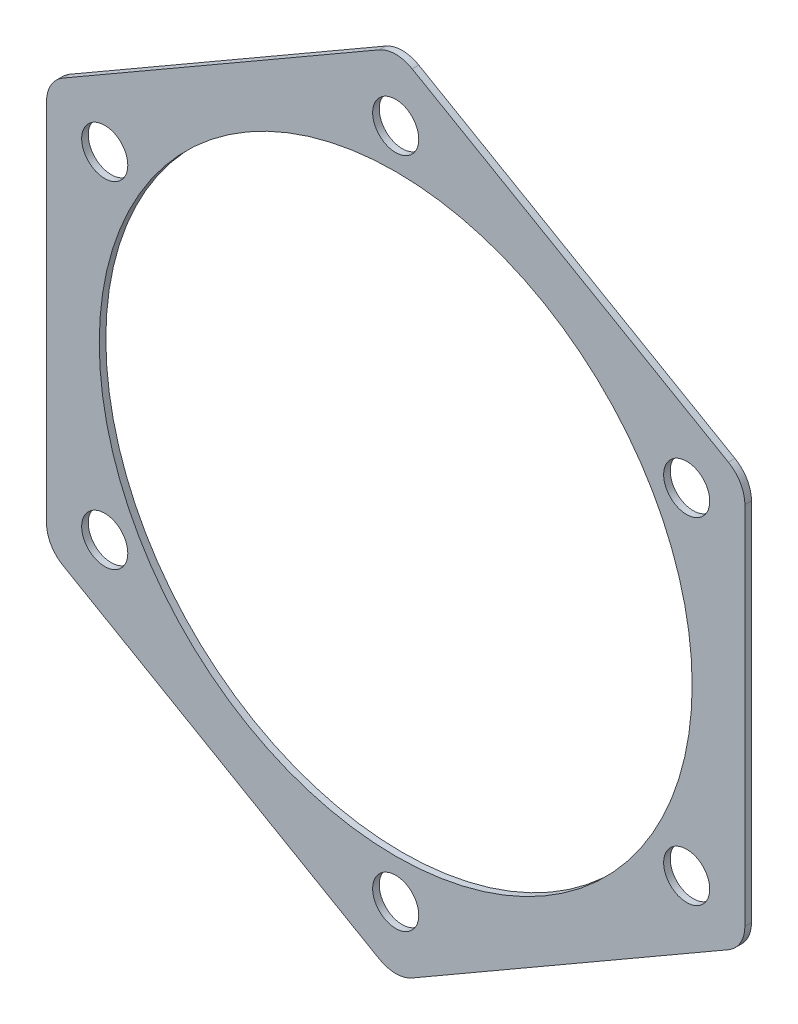
SolidWorks part; units mm, degrees
ref_plane "Front Plane" through (0, 0, 0) normal (0, 0, 1) x (1, 0, 0)
ref_plane "Top Plane" through (0, 0, 0) normal (0, 1, 0) x (1, 0, 0)
ref_plane "Right Plane" through (0, 0, 0) normal (1, 0, 0) x (0, 0, -1)
sketch "Sketch1" plane through (0, 0, 0) normal (0, 0, 1) x (1, 0, 0)
  line L0 (0, 61.1991) -> (0, -61.1991) construction
  line L1 (0, 61.1991) -> (-53, 30.5996)
  line L2 (-53, 30.5996) -> (-53, -30.5996)
  line L3 (-53, -30.5996) -> (0, -61.1991)
  line L4 (0, -61.1991) -> (53, -30.5996)
  line L5 (53, -30.5996) -> (53, 30.5996)
  line L6 (53, 30.5996) -> (0, 61.1991)
  line L7 (-53, 0) -> (53, 0) construction
  line L8 (-44.1673, 25.5) -> (0, 0) construction
  line L9 (0, 0) -> (44.1673, 25.5) construction
  line L10 (0, 0) -> (-44.1673, -25.5) construction
  line L11 (0, 0) -> (44.1673, -25.5) construction
  circle A0 centre (0, 0) radius 53 construction
  circle A1 centre (0, 0) radius 45
  circle A2 centre (0, 0) radius 51 construction
  circle A3 centre (0, 51) radius 3.5
  circle A9 centre (44.1673, 25.5) radius 3.5
  circle A10 centre (44.1673, -25.5) radius 3.5
  circle A11 centre (0, -51) radius 3.5
  circle A12 centre (-44.1673, -25.5) radius 3.5
  circle A13 centre (-44.1673, 25.5) radius 3.5
  point P15 (0, 0)
  point P26 (0.3422, 0.6021)
  point P27 (0, 0)
  point P28 (0, 0)
  point P29 (0, 0)
  dimension "D2" = 90
  dimension "D3" = 102
  dimension "D4" = 7
  dimension "D1" = 106
  dimension "D6" = 30
  dimension "D5" = 6
extrude "Boss-Extrude1" add sketch "Sketch1" along normal blind 1
fillet "Fillet1" radius 5 6 edges at (53, -30.5996, 0.5) (0, -61.1991, 0.5) (-53, -30.5996, 0.5) (-53, 30.5996, 0.5) (53, 30.5996, 0.5) (0, 61.1991, 0.5)
